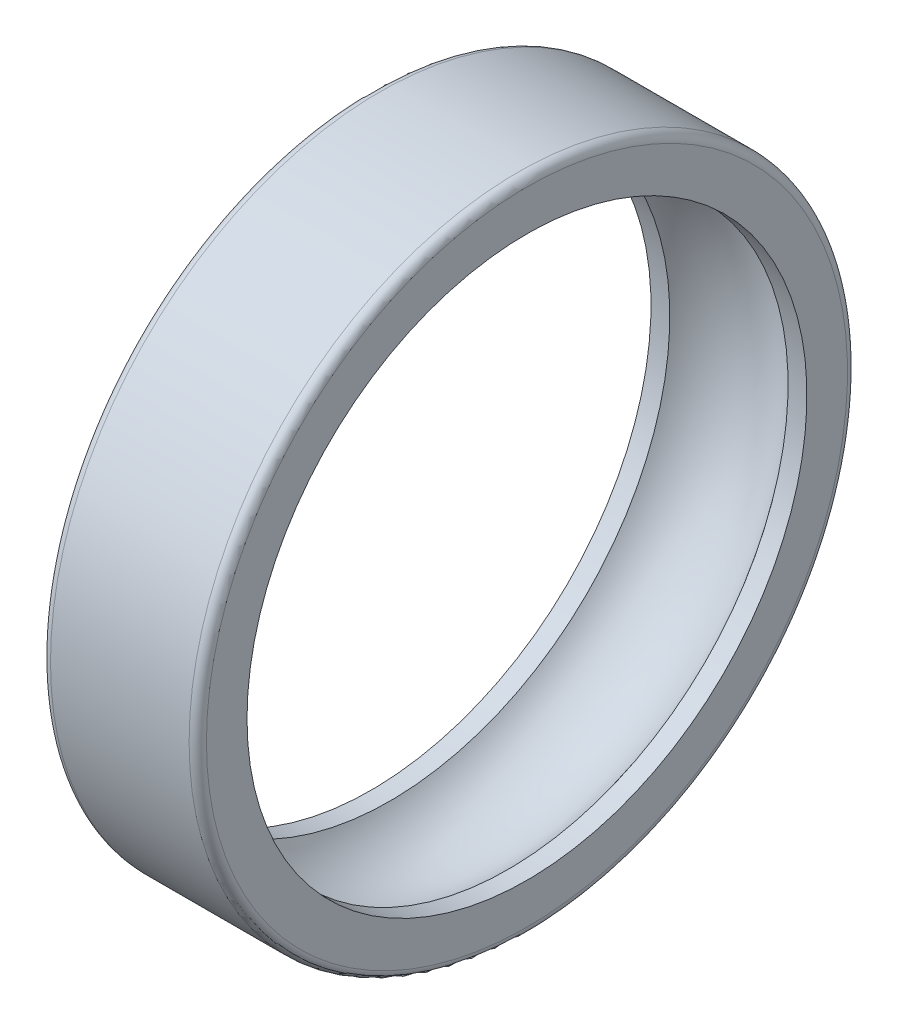
SolidWorks part; units mm, degrees
ref_plane "Front Plane" through (0, 0, 0) normal (0, 0, 1) x (1, 0, 0)
ref_plane "Top Plane" through (0, 0, 0) normal (0, 1, 0) x (1, 0, 0)
ref_plane "Right Plane" through (0, 0, 0) normal (1, 0, 0) x (0, 0, -1)
sketch "Sketch2" plane through (0, 0, 0) normal (0, 0, 1) x (1, 0, 0)
  line L0 (-12.9935, 0) -> (24.917, 0) construction
  line L1 (0, 112.9583) -> (0, 0) construction
  line L2 (22.5, 80.79) -> (17.0682, 80.79)
  line L3 (22.5, 80.79) -> (22.5, 95)
  line L4 (22.5, 95) -> (-22.5, 95)
  line L5 (-22.5, 80.79) -> (-22.5, 95)
  line L6 (22.5, 80.79) -> (-22.5, 95) construction
  line L7 (22.5, 95) -> (-22.5, 80.79) construction
  line L8 (-17.0682, 80.79) -> (-22.5, 80.79)
  arc A0 (-17.0682, 80.79) -> (17.0682, 80.79) centre (0, 68.99) cw
  point P2 (0, 112.9583)
  point P3 (0, 87.895)
  dimension "D5" = 20.75
  dimension "D1" = 45
  dimension "D2" = 80.79
  dimension "D3" = 95
  dimension "D4" = 11.8
revolve "Revolve1" add sketch "Sketch2" angle 360 about L0
fillet "Fillet1" radius 2.5 2 edges at (22.5, 0, 95) (-22.5, 0, 95)
